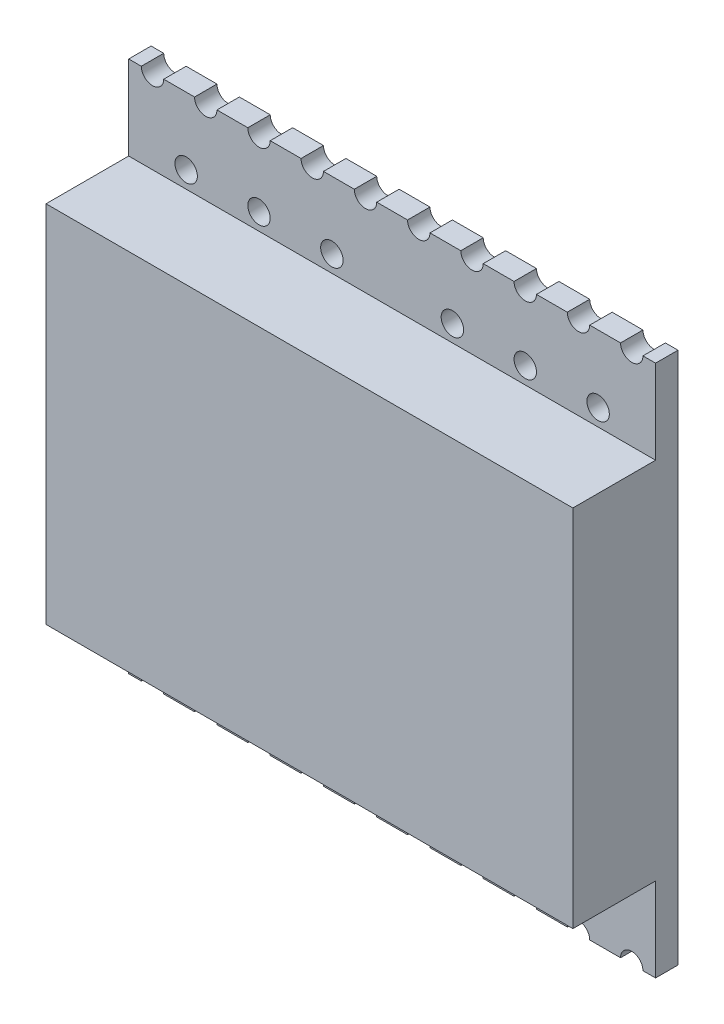
SolidWorks part; units mm, degrees
ref_plane "Спереди" through (0, 0, 0) normal (0, 0, 1) x (1, 0, 0)
ref_plane "Сверху" through (0, 0, 0) normal (0, 1, 0) x (1, 0, 0)
ref_plane "Справа" through (0, 0, 0) normal (1, 0, 0) x (0, 0, -1)
sketch "Эскиз1" plane through (0, 0, 0) normal (0, 0, 1) x (1, 0, 0)
  line L1 (-9.4, -9.5) -> (9.4, -9.5)
  line L2 (-9.4, -9.5) -> (-9.4, 9.5)
  line L3 (-9.4, 9.5) -> (9.4, 9.5)
  line L4 (9.4, -9.5) -> (9.4, 9.5)
  line L5 (-9.4, -9.5) -> (9.4, 9.5) construction
  line L6 (-9.4, 9.5) -> (9.4, -9.5) construction
  point P0 (0, 0)
  dimension "D1" = 18.8
  dimension "D2" = 19
extrude "Бобышка-Вытянуть1" add sketch "Эскиз1" along normal blind 0.8
sketch "Эскиз2" plane through (0, 0, 0.8) normal (0, 0, 1) x (1, 0, 0)
  line L0 (9.4, -9.5) -> (9.4, 9.5) construction
  line L1 (-9.4, -6.5) -> (9.4, -6.5)
  line L2 (-9.4, -6.5) -> (-9.4, 6.5)
  line L3 (-9.4, 6.5) -> (9.4, 6.5)
  line L4 (9.4, -6.5) -> (9.4, 6.5)
  line L5 (-9.4, -6.5) -> (9.4, 6.5) construction
  line L6 (-9.4, 6.5) -> (9.4, -6.5) construction
  point P0 (0, 0)
  dimension "D1" = 13
extrude "Бобышка-Вытянуть2" add sketch "Эскиз2" along normal blind 2.95
sketch "Эскиз3" plane through (0, 0, 0.8) normal (0, 0, 1) x (1, 0, 0)
  line L0 (-9.4, -9.5) -> (9.4, -9.5) construction
  line L1 (-8.95, -9.5) -> (-8.15, -9.5)
  arc A0 (-8.95, -9.5) -> (-8.15, -9.5) centre (-8.55, -9.5) cw
  dimension "D1" = 0.4
  dimension "D2" = 0.85
extrude "Вырез-Вытянуть1" cut sketch "Эскиз3" against normal through all both and the other way through all
mirror "Зеркальное отражение1" about plane through (0, 0, 0) normal (0, 1, 0) of "Вырез-Вытянуть1"
pattern_linear "Линейный массив1" count 10 spacing 1.9 along (1, 0, 0) of "Зеркальное отражение1", "Вырез-Вытянуть1"
sketch "Эскиз4" plane through (0, 0, 0.8) normal (0, 0, 1) x (1, 0, 0)
  circle A0 centre (-2.15, -7.1) radius 0.4
  point P2 (0, 0)
  dimension "D2" = 0.8
  dimension "D1" = 7.1
  dimension "D3" = 2.15
extrude "Вырез-Вытянуть2" cut sketch "Эскиз4" against normal through all both and the other way through all
pattern_linear "Линейный массив2" count 3 spacing 2.6 along (-1, 0, 0) of "Вырез-Вытянуть2"
mirror "Зеркальное отражение2" about plane through (0, 0, 0) normal (0, 1, 0) of "Линейный массив2", "Вырез-Вытянуть2"
mirror "Зеркальное отражение3" about plane through (0, 0, 0) normal (1, 0, 0) of "Зеркальное отражение2", "Линейный массив2", "Вырез-Вытянуть2"
